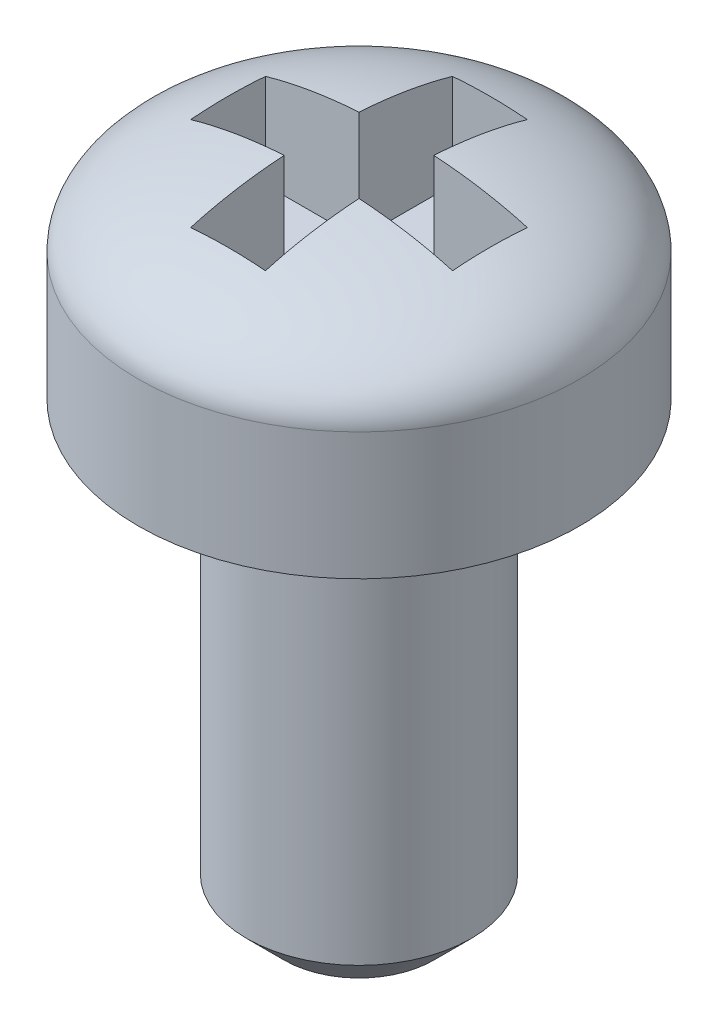
SolidWorks part; units mm, degrees
ref_plane "Front Plane" through (0, 0, 0) normal (0, 0, 1) x (1, 0, 0)
ref_plane "Top Plane" through (0, 0, 0) normal (0, 1, 0) x (1, 0, 0)
ref_plane "Right Plane" through (0, 0, 0) normal (1, 0, 0) x (0, 0, -1)
sketch "Sketch1" plane through (0, 0, 0) normal (0, 0, 1) x (1, 0, 0)
  line L0 (-1.5, -2.85) -> (-1.5, -8.35)
  line L1 (-1, -8.85) -> (0, -8.85)
  line L2 (-1.5, -2.85) -> (-2.95, -2.85)
  line L3 (-2.95, -2.85) -> (-2.95, -1.15)
  line L4 (0, 0) -> (0, -8.85)
  line L5 (-1.5, -8.35) -> (-1, -8.85)
  ellipse E0 centre (0, -1.15) end of major axis (-2.95, -1.15) minor radius 1.15 (0, 0) -> (-2.95, -1.15) ccw
  point P1 (-1.5, -8.85)
  point P12 (0, 0)
  point P14 (0, 0)
  dimension "D1" = 2.95
  dimension "D2" = 1.5
  dimension "D3" = 2.85
  dimension "D4" = 1.7
  dimension "D5" = 6
revolve "Revolve1" add sketch "Sketch1" angle 360 about L4
sketch "Sketch2" plane through (0, 0, 0) normal (0, 1, 0) x (1, 0, 0)
  line L0 (-1.75, 0.5) -> (1.75, -0.5) construction
  line L1 (-1.75, 0.5) -> (-0.5, 0.5)
  line L2 (-1.75, 0.5) -> (-1.75, -0.5)
  line L3 (-1.75, -0.5) -> (-0.5, -0.5)
  line L4 (1.75, 0.5) -> (1.75, -0.5)
  line L5 (-0.5, 1.75) -> (0.5, 1.75)
  line L6 (-0.5, 1.75) -> (-0.5, 0.5)
  line L7 (-0.5, -1.75) -> (0.5, -1.75)
  line L8 (0.5, 1.75) -> (0.5, 0.5)
  line L9 (0.5, -1.75) -> (-0.5, 1.75) construction
  line L10 (-0.5, -0.5) -> (-0.5, -1.75)
  line L11 (0.5, 0.5) -> (1.75, 0.5)
  line L12 (0.5, -0.5) -> (0.5, -1.75)
  line L13 (0.5, -0.5) -> (1.75, -0.5)
  point P8 (-0.4324, 1.7491)
  dimension "D1" = 3.5
  dimension "D2" = 1
extrude "Cut-Extrude1" cut sketch "Sketch2" against normal blind 1.5
